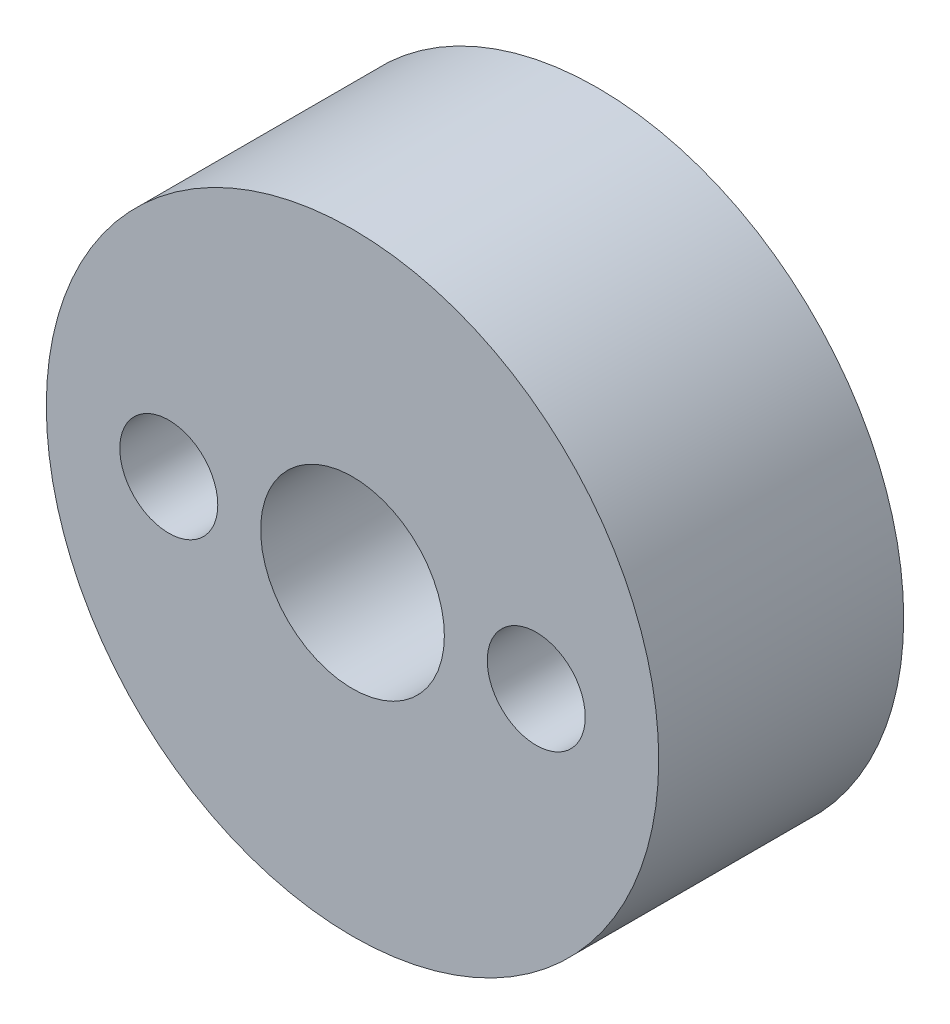
SolidWorks part; units mm, degrees
ref_plane "正面" through (0, 0, 0) normal (0, 0, 1) x (1, 0, 0)
ref_plane "平面" through (0, 0, 0) normal (0, 1, 0) x (1, 0, 0)
ref_plane "右側面" through (0, 0, 0) normal (1, 0, 0) x (0, 0, -1)
sketch "ｽｹｯﾁ1" plane through (0, 0, 0) normal (0, 0, 1) x (1, 0, 0)
  circle A0 centre (0, 0) radius 3
  circle A1 centre (0, 0) radius 6 construction
  circle A2 centre (0, 0) radius 10
  circle A3 centre (-6, 0) radius 1.6
  circle A4 centre (6, 0) radius 1.6
  dimension "D1" = 20
  dimension "D2" = 12
  dimension "D3" = 6
  dimension "D4" = 3.2
extrude "ﾎﾞｽ - 押し出し1" add sketch "ｽｹｯﾁ1" along normal blind 8
